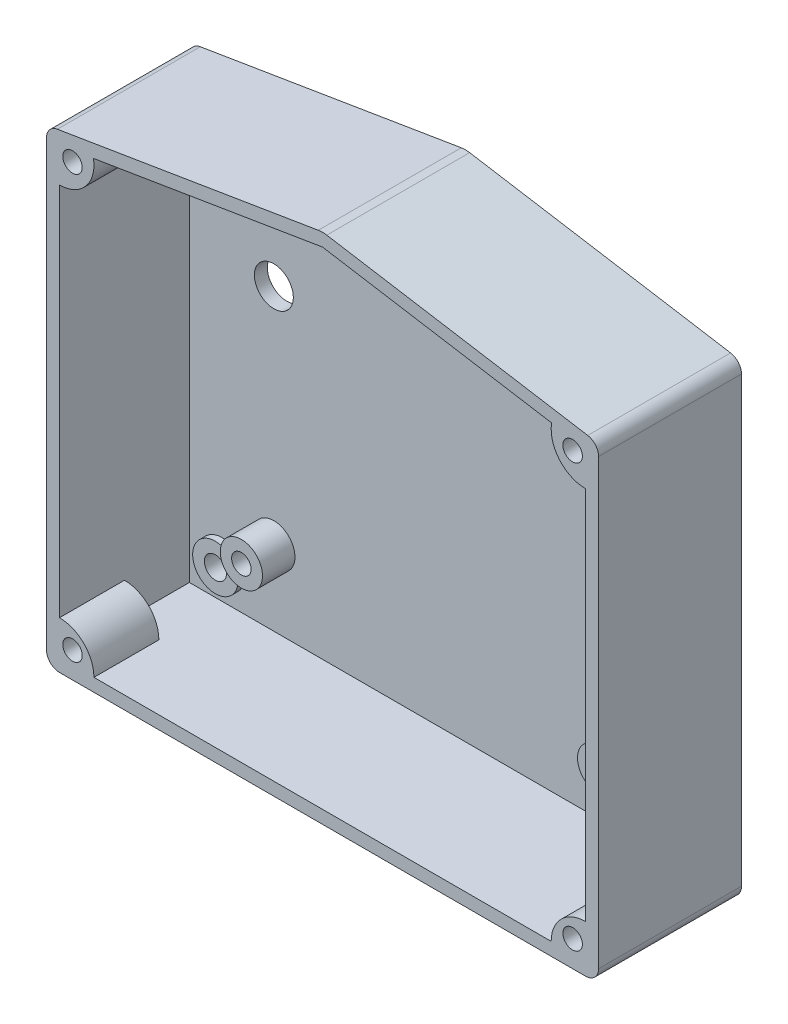
SolidWorks part; units mm, degrees
ref_plane "Piano frontale" through (0, 0, 0) normal (0, 0, 1) x (1, 0, 0)
ref_plane "Piano superiore" through (0, 0, 0) normal (0, 1, 0) x (1, 0, 0)
ref_plane "Piano destro" through (0, 0, 0) normal (1, 0, 0) x (0, 0, -1)
sketch "Schizzo6" plane through (0, 0, 0) normal (0, 0, 1) x (1, 0, 0)
  line L0 (-42.5, 36) -> (0, 43)
  line L2 (-42.5, 36) -> (-42.5, -36)
  line L3 (-42.5, -36) -> (42.5, -36)
  line L4 (42.5, 36) -> (42.5, -36)
  line L5 (-42.5, 36) -> (42.5, -36) construction
  line L6 (-42.5, -36) -> (42.5, 36) construction
  line L7 (0, 43) -> (42.5, 36)
  circle A1 centre (-35.5, 29) radius 1.7
  circle A2 centre (35.5, 29) radius 1.7
  circle A3 centre (35.5, -29) radius 1.7
  circle A4 centre (-35.5, -29) radius 1.7
  point P0 (0, 0)
  dimension "D1" = 3.4
  dimension "D3" = 7
  dimension "D2" = 7
  dimension "D4" = 7
  dimension "D5" = 7
  dimension "D6" = 7
  dimension "D7" = 85
  dimension "D8" = 72
extrude "Estrusione-Estrusione1" add sketch "Schizzo6" along normal blind 2
sketch "Schizzo8" plane through (0, 0, 2) normal (0, 0, 1) x (1, 0, 0)
  line L0 (-40.5, 34.3025) -> (-40.5, -34)
  line L1 (-40.5, -34) -> (40.5, -34)
  line L2 (40.5, -34) -> (40.5, 34.3025)
  line L5 (-42.5, 36) -> (0, 43)
  line L6 (0, 43) -> (42.5, 36)
  line L7 (42.5, 36) -> (42.5, -36)
  line L8 (42.5, -36) -> (-42.5, -36)
  line L9 (-42.5, -36) -> (-42.5, 36)
  line L10 (0, 40.9731) -> (-40.5, 34.3025)
  line L11 (0, 40.9731) -> (40.5, 34.3025)
  dimension "D4" = 2
  dimension "D1" = 2
  dimension "D2" = 2
  dimension "D3" = 2
  dimension "D5" = 2
extrude "Estrusione-Estrusione2" add sketch "Schizzo8" along normal blind 20
sketch "Schizzo9" plane through (0, 0, 2) normal (0, 0, 1) x (1, 0, 0)
  circle A0 centre (-35.5, 29) radius 3.5
  circle A1 centre (-35.5, -29) radius 3.5
  circle A2 centre (35.5, -29) radius 3.5
  circle A3 centre (35.5, 29) radius 3.5
  circle A4 centre (-35.5, 29) radius 1.7
  circle A5 centre (35.5, 29) radius 1.7
  circle A6 centre (35.5, -29) radius 1.7
  circle A7 centre (-35.5, -29) radius 1.7
  dimension "D1" = 7
  dimension "D2" = 3.4
extrude "Estrusione-Fori Chassis" add sketch "Schizzo9" along normal blind 1
sketch "Schizzo10" plane through (0, 0, 2) normal (0, 0, 1) x (1, 0, 0)
  line L1 (-42.5, 36) -> (-42.5, -36) construction
  line L2 (-40.5, -34) -> (40.5, -34) construction
  line L4 (40.5, -34) -> (40.5, 34.3025) construction
  circle A0 centre (-5.5, 28.5) radius 1.5
  circle A1 centre (-27.5, -22.5) radius 1.5
  circle A2 centre (27.5, -22.5) radius 1.5
  circle A3 centre (-27.5, -22.5) radius 3.25
  circle A4 centre (-5.5, 28.5) radius 3.25
  circle A5 centre (27.5, -22.5) radius 3.25
  dimension "D1" = 3
  dimension "D6" = 6.5
  dimension "D4" = 51
  dimension "D2" = 55
  dimension "D3" = 13
  dimension "D5" = 11.5
  dimension "D7" = 37
extrude "Estrusione-Fori PCB" add sketch "Schizzo10" along normal blind 5
fillet "Raccordo1" radius 4 1 edges at (0, 43, 11)
fillet "Raccordo2" radius 2 1 edges at (42.5, 36, 11)
fillet "Raccordo3" radius 2 1 edges at (-42.5, 36, 11)
fillet "Raccordo4" radius 2 1 edges at (-42.5, -36, 11)
fillet "Raccordo5" radius 2 1 edges at (42.5, -36, 11)
sketch "Schizzo11" plane through (0, 0, 22) normal (0, 0, 1) x (1, 0, 0)
  line L0 (0, 40.9731) -> (-40.5, 34.3025) construction
  line L1 (-40.5, 34.3025) -> (-40.5, -34) construction
  line L2 (40.5, -34) -> (40.5, 34.3025) construction
  line L3 (40.5, 34.3025) -> (0, 40.9731) construction
  line L4 (-40.5, -34) -> (40.5, -34) construction
  line L5 (-35.2705, 35.1638) -> (-40.5, 34.3025)
  line L6 (-40.5, 34.3025) -> (-40.5, 29.0025)
  line L7 (-35.2, -34) -> (-40.5, -34)
  line L8 (-40.5, -34) -> (-40.5, -28.7)
  line L9 (40.5, -28.7) -> (40.5, -34)
  line L10 (40.5, -34) -> (35.2, -34)
  line L11 (35.2705, 35.1638) -> (40.5, 34.3025)
  line L12 (40.5, 34.3025) -> (40.5, 29.0025)
  arc A0 (-35.2705, 35.1638) -> (-40.5, 29.0025) centre (-40.5, 34.3025) cw
  arc A1 (40.5, 29.0025) -> (35.2705, 35.1638) centre (40.5, 34.3025) cw
  arc A2 (40.5, -28.7) -> (35.2, -34) centre (40.5, -34) ccw
  arc A3 (-40.5, -28.7) -> (-35.2, -34) centre (-40.5, -34) cw
  dimension "D1" = 5.3
extrude "Estrusione-Estrusione3" add sketch "Schizzo11" against normal blind 10
hole_wizard "Foro per Vite M2-1" positions "Schizzo12" profile "Schizzo13" hole size "M2" standard "Ansi Metric"
sketch "Schizzo12" plane through (0, 0, 22) normal (0, 0, 1) x (1, 0, 0)
  line L5 (-42.5, 34.3025) -> (-42.5, -34) construction
  line L6 (42.5, -34) -> (42.5, 34.3025) construction
  line L7 (-40.5, -36) -> (40.5, -36) construction
  point P0 (-38.5, 33.0759)
  point P3 (-38.5, -32)
  point P5 (38.5, -32)
  point P7 (38.5, 33.0759)
  dimension "D1" = 3.2
  dimension "D2" = 4
  dimension "D3" = 4
  dimension "D4" = 3.2
  dimension "D5" = 4
  dimension "D6" = 4
  dimension "D7" = 4
  dimension "D8" = 4
sketch "Schizzo13" plane through (-38.5, 33.0759, 22) normal (1, 0, 0) x (0, -1, 0)
  line L0 (0, 0) -> (0, 10)
  line L1 (0, 10) -> (1.5, 10)
  line L2 (1.5, 10) -> (1.5, 0)
  line L5 (1.5, 0) -> (0, 0)
  line L11 (0, -6.35) -> (0, 107.95) construction
  dimension "Thru Hole Dia." = 3
  dimension "Thru Hole Depth" = 10
sketch "Schizzo15" plane through (0, 0, 2) normal (0, 0, 1) x (1, 0, 0)
  line L0 (42.5, -34) -> (42.5, 34.3025) construction
  line L1 (-40.5, -36) -> (40.5, -36) construction
  line L2 (-42.5, 34.3025) -> (-42.5, -34) construction
  circle A0 centre (27.5, 12) radius 3.5
  circle A1 centre (-27.5, 12) radius 3
  dimension "D1" = 7
  dimension "D3" = 48
  dimension "D4" = 6
  dimension "D2" = 15
  dimension "D5" = 15
extrude "Taglio-Fori Passaggio Cavi" cut sketch "Schizzo15" against normal up to next
